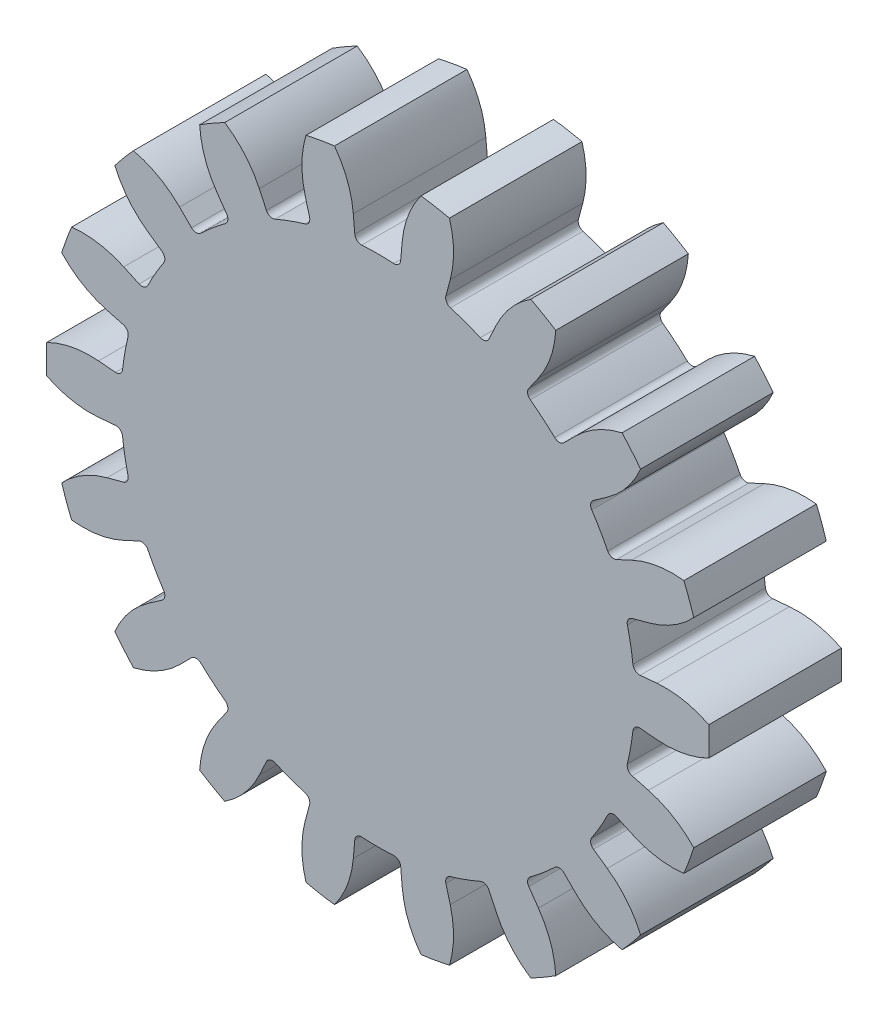
SolidWorks part; units mm, degrees
ref_plane "Front Plane" through (0, 0, 0) normal (0, 0, 1) x (1, 0, 0)
ref_plane "Top Plane" through (0, 0, 0) normal (0, 1, 0) x (1, 0, 0)
ref_plane "Right Plane" through (0, 0, 0) normal (1, 0, 0) x (0, 0, -1)
sketch "Sketch1" plane through (0, 0, 0) normal (0, 0, 1) x (1, 0, 0)
  line L0 (0, 0) -> (38.1613, 6.7289)
  line L1 (0, 0) -> (38.1613, -6.7289)
  line L4 (42.1241, 3.6854) -> (38.6025, 3.3773)
  line L6 (42.1241, -3.6854) -> (38.6025, -3.3773)
  arc A3 (42.1241, 3.6854) -> (49.9524, 2.181) centre (43.3938, -10.8274) cw
  arc A4 (38.1613, 6.7289) -> (38.6025, 3.3773) centre (0, 0) cw
  arc A5 (49.9524, 2.181) -> (49.9524, -2.181) centre (0, 0) cw
  arc A6 (42.1241, -3.6854) -> (49.9524, -2.181) centre (43.3938, 10.8274) ccw
  arc A8 (38.1613, -6.7289) -> (38.6025, -3.3773) centre (0, 0) ccw
extrude "Boss-Extrude1" add sketch "Sketch1" along normal blind 20
fillet "Fillet1" radius 1 2 edges at (38.6025, 3.3773, 10) (38.6025, -3.3773, 10)
pattern_circular "CirPattern1" count 18 over 360 about axis through (0, 0, 0) along (0, 0, 1) of "Boss-Extrude1"
fillet "Fillet2" radius 1 34 edges at (-38.6025, -3.3773, 10) (-37.4296, -10.0292, 10) (-35.1194, -16.3765, 10) (-31.7421, -22.2261, 10) (-27.4004, -27.4004, 10) (-22.2261, -31.7421, 10) (-16.3765, -35.1194, 10) (-10.0292, -37.4296, 10) (-3.3773, -38.6025, 10) (3.3773, -38.6025, 10) (10.0292, -37.4296, 10) (16.3765, -35.1194, 10) (22.2261, -31.7421, 10) (27.4004, -27.4004, 10) (31.7421, -22.2261, 10) (35.1194, -16.3765, 10) (37.4296, -10.0292, 10) (37.4296, 10.0292, 10) (35.1194, 16.3765, 10) (31.7421, 22.2261, 10) (27.4004, 27.4004, 10) (22.2261, 31.7421, 10) (16.3765, 35.1194, 10) (10.0292, 37.4296, 10) (3.3773, 38.6025, 10) (-3.3773, 38.6025, 10) (-10.0292, 37.4296, 10) (-16.3765, 35.1194, 10) (-22.2261, 31.7421, 10) (-27.4004, 27.4004, 10) (-31.7421, 22.2261, 10) (-35.1194, 16.3765, 10) (-37.4296, 10.0292, 10) (-38.6025, 3.3773, 10)
